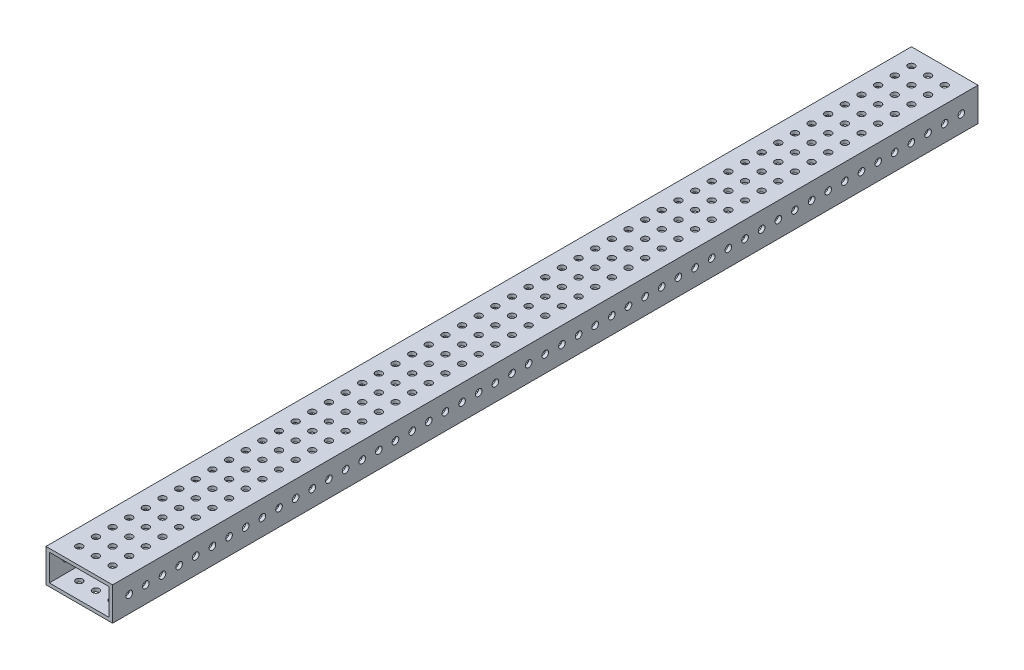
SolidWorks part; units mm, degrees
ref_plane "Front Plane" through (0, 0, 0) normal (0, 0, 1) x (1, 0, 0)
ref_plane "Top Plane" through (0, 0, 0) normal (0, 1, 0) x (1, 0, 0)
ref_plane "Right Plane" through (0, 0, 0) normal (1, 0, 0) x (0, 0, -1)
sketch "Sketch1" plane through (0, 0, 0) normal (0, 0, 1) x (1, 0, 0)
  line L1 (-19.3121, -15.3005) -> (31.4879, -15.3005)
  line L2 (-19.3121, -15.3005) -> (-19.3121, 10.0995)
  line L3 (-19.3121, 10.0995) -> (31.4879, 10.0995)
  line L4 (31.4879, -15.3005) -> (31.4879, 10.0995)
  line L5 (-19.3121, -15.3005) -> (31.4879, 10.0995) construction
  line L6 (-19.3121, 10.0995) -> (31.4879, -15.3005) construction
  line L7 (-16.7721, -12.7605) -> (28.9479, -12.7605)
  line L8 (-16.7721, -12.7605) -> (-16.7721, 7.5595)
  line L9 (-16.7721, 7.5595) -> (28.9479, 7.5595)
  line L10 (28.9479, -12.7605) -> (28.9479, 7.5595)
  line L11 (-16.7721, -12.7605) -> (28.9479, 7.5595) construction
  line L12 (-16.7721, 7.5595) -> (28.9479, -12.7605) construction
  point P0 (6.0879, -2.6005)
  point P5 (6.0879, -2.6005)
  dimension "D1" = 2.54
  dimension "D2" = 2.54
  dimension "D3" = 45.72
  dimension "D4" = 20.32
extrude "Boss-Extrude1" add sketch "Sketch1" along normal blind 660.4
sketch "Sketch2" plane through (31.4879, 0, 0) normal (1, 0, 0) x (0, 0, -1)
  line L0 (-660.4, -15.3005) -> (-660.4, 10.0995) construction
  line L1 (-660.4, 10.0995) -> (0, 10.0995) construction
  circle A0 centre (-647.7, -2.6005) radius 2.54
  circle A1 centre (-635, -2.6005) radius 2.54
  circle A2 centre (-622.3, -2.6005) radius 2.54
  circle A3 centre (-609.6, -2.6005) radius 2.54
  circle A4 centre (-596.9, -2.6005) radius 2.54
  circle A5 centre (-584.2, -2.6005) radius 2.54
  circle A6 centre (-571.5, -2.6005) radius 2.54
  circle A7 centre (-558.8, -2.6005) radius 2.54
  circle A8 centre (-546.1, -2.6005) radius 2.54
  circle A9 centre (-533.4, -2.6005) radius 2.54
  circle A10 centre (-520.7, -2.6005) radius 2.54
  circle A11 centre (-508, -2.6005) radius 2.54
  circle A12 centre (-495.3, -2.6005) radius 2.54
  circle A13 centre (-482.6, -2.6005) radius 2.54
  circle A14 centre (-469.9, -2.6005) radius 2.54
  circle A15 centre (-457.2, -2.6005) radius 2.54
  circle A16 centre (-444.5, -2.6005) radius 2.54
  circle A17 centre (-431.8, -2.6005) radius 2.54
  circle A18 centre (-419.1, -2.6005) radius 2.54
  circle A19 centre (-406.4, -2.6005) radius 2.54
  circle A20 centre (-393.7, -2.6005) radius 2.54
  circle A21 centre (-381, -2.6005) radius 2.54
  circle A22 centre (-368.3, -2.6005) radius 2.54
  circle A23 centre (-355.6, -2.6005) radius 2.54
  circle A24 centre (-342.9, -2.6005) radius 2.54
  circle A25 centre (-330.2, -2.6005) radius 2.54
  circle A26 centre (-317.5, -2.6005) radius 2.54
  circle A27 centre (-304.8, -2.6005) radius 2.54
  circle A28 centre (-292.1, -2.6005) radius 2.54
  circle A29 centre (-279.4, -2.6005) radius 2.54
  circle A30 centre (-266.7, -2.6005) radius 2.54
  circle A31 centre (-254, -2.6005) radius 2.54
  circle A32 centre (-241.3, -2.6005) radius 2.54
  circle A33 centre (-228.6, -2.6005) radius 2.54
  circle A34 centre (-215.9, -2.6005) radius 2.54
  circle A35 centre (-203.2, -2.6005) radius 2.54
  circle A36 centre (-190.5, -2.6005) radius 2.54
  circle A37 centre (-177.8, -2.6005) radius 2.54
  circle A38 centre (-165.1, -2.6005) radius 2.54
  circle A39 centre (-152.4, -2.6005) radius 2.54
  circle A40 centre (-139.7, -2.6005) radius 2.54
  circle A41 centre (-127, -2.6005) radius 2.54
  circle A42 centre (-114.3, -2.6005) radius 2.54
  circle A43 centre (-101.6, -2.6005) radius 2.54
  circle A44 centre (-88.9, -2.6005) radius 2.54
  circle A45 centre (-76.2, -2.6005) radius 2.54
  circle A46 centre (-63.5, -2.6005) radius 2.54
  circle A47 centre (-50.8, -2.6005) radius 2.54
  circle A48 centre (-38.1, -2.6005) radius 2.54
  circle A49 centre (-25.4, -2.6005) radius 2.54
  circle A50 centre (-12.7, -2.6005) radius 2.54
  dimension "D1" = 12.7
  dimension "D2" = 12.7
  dimension "D3" = 51
extrude "Cut-Extrude1" cut sketch "Sketch2" against normal blind 50.8
sketch "Sketch3" plane through (0, 10.0995, 0) normal (0, 1, 0) x (1, 0, 0)
  line L0 (-19.3121, -660.4) -> (-19.3121, 0) construction
  line L1 (31.4879, -660.4) -> (-19.3121, -660.4) construction
  circle A0 centre (-6.6121, -647.7) radius 2.54
  circle A1 centre (6.0879, -647.7) radius 2.54
  circle A2 centre (18.7879, -647.7) radius 2.54
  circle A3 centre (6.0879, -635) radius 2.54
  circle A4 centre (18.7879, -635) radius 2.54
  circle A5 centre (6.0879, -622.3) radius 2.54
  circle A6 centre (18.7879, -622.3) radius 2.54
  circle A7 centre (6.0879, -609.6) radius 2.54
  circle A8 centre (18.7879, -609.6) radius 2.54
  circle A9 centre (6.0879, -596.9) radius 2.54
  circle A10 centre (18.7879, -596.9) radius 2.54
  circle A11 centre (6.0879, -584.2) radius 2.54
  circle A12 centre (18.7879, -584.2) radius 2.54
  circle A13 centre (6.0879, -571.5) radius 2.54
  circle A14 centre (18.7879, -571.5) radius 2.54
  circle A15 centre (6.0879, -558.8) radius 2.54
  circle A16 centre (18.7879, -558.8) radius 2.54
  circle A17 centre (6.0879, -546.1) radius 2.54
  circle A18 centre (18.7879, -546.1) radius 2.54
  circle A19 centre (6.0879, -533.4) radius 2.54
  circle A20 centre (18.7879, -533.4) radius 2.54
  circle A21 centre (6.0879, -520.7) radius 2.54
  circle A22 centre (18.7879, -520.7) radius 2.54
  circle A23 centre (6.0879, -508) radius 2.54
  circle A24 centre (18.7879, -508) radius 2.54
  circle A25 centre (6.0879, -495.3) radius 2.54
  circle A26 centre (18.7879, -495.3) radius 2.54
  circle A27 centre (6.0879, -482.6) radius 2.54
  circle A28 centre (18.7879, -482.6) radius 2.54
  circle A29 centre (6.0879, -469.9) radius 2.54
  circle A30 centre (18.7879, -469.9) radius 2.54
  circle A31 centre (6.0879, -457.2) radius 2.54
  circle A32 centre (18.7879, -457.2) radius 2.54
  circle A33 centre (6.0879, -444.5) radius 2.54
  circle A34 centre (18.7879, -444.5) radius 2.54
  circle A35 centre (6.0879, -431.8) radius 2.54
  circle A36 centre (18.7879, -431.8) radius 2.54
  circle A37 centre (6.0879, -419.1) radius 2.54
  circle A38 centre (18.7879, -419.1) radius 2.54
  circle A39 centre (6.0879, -406.4) radius 2.54
  circle A40 centre (18.7879, -406.4) radius 2.54
  circle A41 centre (6.0879, -393.7) radius 2.54
  circle A42 centre (18.7879, -393.7) radius 2.54
  circle A43 centre (6.0879, -381) radius 2.54
  circle A44 centre (18.7879, -381) radius 2.54
  circle A45 centre (6.0879, -368.3) radius 2.54
  circle A46 centre (18.7879, -368.3) radius 2.54
  circle A47 centre (6.0879, -355.6) radius 2.54
  circle A48 centre (18.7879, -355.6) radius 2.54
  circle A49 centre (6.0879, -342.9) radius 2.54
  circle A50 centre (18.7879, -342.9) radius 2.54
  circle A51 centre (6.0879, -330.2) radius 2.54
  circle A52 centre (18.7879, -330.2) radius 2.54
  circle A53 centre (6.0879, -317.5) radius 2.54
  circle A54 centre (18.7879, -317.5) radius 2.54
  circle A55 centre (6.0879, -304.8) radius 2.54
  circle A56 centre (18.7879, -304.8) radius 2.54
  circle A57 centre (6.0879, -292.1) radius 2.54
  circle A58 centre (18.7879, -292.1) radius 2.54
  circle A59 centre (6.0879, -279.4) radius 2.54
  circle A60 centre (18.7879, -279.4) radius 2.54
  circle A61 centre (6.0879, -266.7) radius 2.54
  circle A62 centre (18.7879, -266.7) radius 2.54
  circle A63 centre (6.0879, -254) radius 2.54
  circle A64 centre (18.7879, -254) radius 2.54
  circle A65 centre (6.0879, -241.3) radius 2.54
  circle A66 centre (18.7879, -241.3) radius 2.54
  circle A67 centre (6.0879, -228.6) radius 2.54
  circle A68 centre (18.7879, -228.6) radius 2.54
  circle A69 centre (6.0879, -215.9) radius 2.54
  circle A70 centre (18.7879, -215.9) radius 2.54
  circle A71 centre (6.0879, -203.2) radius 2.54
  circle A72 centre (18.7879, -203.2) radius 2.54
  circle A73 centre (6.0879, -190.5) radius 2.54
  circle A74 centre (18.7879, -190.5) radius 2.54
  circle A75 centre (6.0879, -177.8) radius 2.54
  circle A76 centre (18.7879, -177.8) radius 2.54
  circle A77 centre (6.0879, -165.1) radius 2.54
  circle A78 centre (18.7879, -165.1) radius 2.54
  circle A79 centre (6.0879, -152.4) radius 2.54
  circle A80 centre (18.7879, -152.4) radius 2.54
  circle A81 centre (6.0879, -139.7) radius 2.54
  circle A82 centre (18.7879, -139.7) radius 2.54
  circle A83 centre (6.0879, -127) radius 2.54
  circle A84 centre (18.7879, -127) radius 2.54
  circle A85 centre (6.0879, -114.3) radius 2.54
  circle A86 centre (18.7879, -114.3) radius 2.54
  circle A87 centre (6.0879, -101.6) radius 2.54
  circle A88 centre (18.7879, -101.6) radius 2.54
  circle A89 centre (6.0879, -88.9) radius 2.54
  circle A90 centre (18.7879, -88.9) radius 2.54
  circle A91 centre (6.0879, -76.2) radius 2.54
  circle A92 centre (18.7879, -76.2) radius 2.54
  circle A93 centre (6.0879, -63.5) radius 2.54
  circle A94 centre (18.7879, -63.5) radius 2.54
  circle A95 centre (6.0879, -50.8) radius 2.54
  circle A96 centre (18.7879, -50.8) radius 2.54
  circle A97 centre (6.0879, -38.1) radius 2.54
  circle A98 centre (18.7879, -38.1) radius 2.54
  circle A99 centre (6.0879, -25.4) radius 2.54
  circle A100 centre (18.7879, -25.4) radius 2.54
  circle A101 centre (6.0879, -12.7) radius 2.54
  circle A102 centre (18.7879, -12.7) radius 2.54
  circle A103 centre (-6.6121, -635) radius 2.54
  circle A104 centre (-6.6121, -622.3) radius 2.54
  circle A105 centre (-6.6121, -609.6) radius 2.54
  circle A106 centre (-6.6121, -596.9) radius 2.54
  circle A107 centre (-6.6121, -584.2) radius 2.54
  circle A108 centre (-6.6121, -571.5) radius 2.54
  circle A109 centre (-6.6121, -558.8) radius 2.54
  circle A110 centre (-6.6121, -546.1) radius 2.54
  circle A111 centre (-6.6121, -533.4) radius 2.54
  circle A112 centre (-6.6121, -520.7) radius 2.54
  circle A113 centre (-6.6121, -508) radius 2.54
  circle A114 centre (-6.6121, -495.3) radius 2.54
  circle A115 centre (-6.6121, -482.6) radius 2.54
  circle A116 centre (-6.6121, -469.9) radius 2.54
  circle A117 centre (-6.6121, -457.2) radius 2.54
  circle A118 centre (-6.6121, -444.5) radius 2.54
  circle A119 centre (-6.6121, -431.8) radius 2.54
  circle A120 centre (-6.6121, -419.1) radius 2.54
  circle A121 centre (-6.6121, -406.4) radius 2.54
  circle A122 centre (-6.6121, -393.7) radius 2.54
  circle A123 centre (-6.6121, -381) radius 2.54
  circle A124 centre (-6.6121, -368.3) radius 2.54
  circle A125 centre (-6.6121, -355.6) radius 2.54
  circle A126 centre (-6.6121, -342.9) radius 2.54
  circle A127 centre (-6.6121, -330.2) radius 2.54
  circle A128 centre (-6.6121, -317.5) radius 2.54
  circle A129 centre (-6.6121, -304.8) radius 2.54
  circle A130 centre (-6.6121, -292.1) radius 2.54
  circle A131 centre (-6.6121, -279.4) radius 2.54
  circle A132 centre (-6.6121, -266.7) radius 2.54
  circle A133 centre (-6.6121, -254) radius 2.54
  circle A134 centre (-6.6121, -241.3) radius 2.54
  circle A135 centre (-6.6121, -228.6) radius 2.54
  circle A136 centre (-6.6121, -215.9) radius 2.54
  circle A137 centre (-6.6121, -203.2) radius 2.54
  circle A138 centre (-6.6121, -190.5) radius 2.54
  circle A139 centre (-6.6121, -177.8) radius 2.54
  circle A140 centre (-6.6121, -165.1) radius 2.54
  circle A141 centre (-6.6121, -152.4) radius 2.54
  circle A142 centre (-6.6121, -139.7) radius 2.54
  circle A143 centre (-6.6121, -127) radius 2.54
  circle A144 centre (-6.6121, -114.3) radius 2.54
  circle A145 centre (-6.6121, -101.6) radius 2.54
  circle A146 centre (-6.6121, -88.9) radius 2.54
  circle A147 centre (-6.6121, -76.2) radius 2.54
  circle A148 centre (-6.6121, -63.5) radius 2.54
  circle A149 centre (-6.6121, -50.8) radius 2.54
  circle A150 centre (-6.6121, -38.1) radius 2.54
  circle A151 centre (-6.6121, -25.4) radius 2.54
  circle A152 centre (-6.6121, -12.7) radius 2.54
  dimension "D1" = 12.7
  dimension "D2" = 12.7
  dimension "D3" = 3
  dimension "D4" = 51
extrude "Cut-Extrude2" cut sketch "Sketch3" against normal blind 25.4
